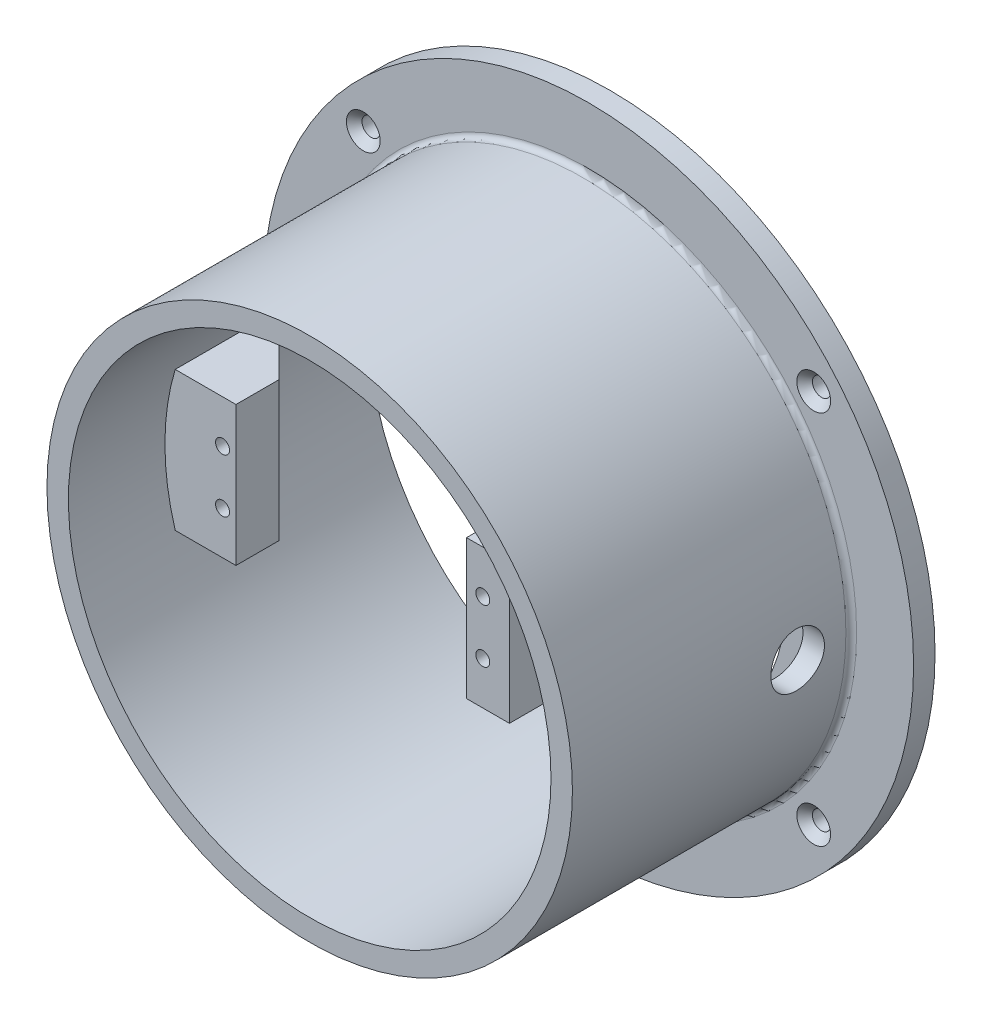
SolidWorks part; units mm, degrees
material "Acrylic (Medium-high impact)"
ref_plane "Front Plane" through (0, 0, 0) normal (0, 0, 1) x (1, 0, 0)
ref_plane "Top Plane" through (0, 0, 0) normal (0, 1, 0) x (1, 0, 0)
ref_plane "Right Plane" through (0, 0, 0) normal (1, 0, 0) x (0, 0, -1)
sketch "Sketch1" plane through (0, 0, 0) normal (0, 0, 1) x (1, 0, 0)
  circle A0 centre (0, 0) radius 60.625
  circle A1 centre (0, 0) radius 45
  dimension "D1" = 90
  dimension "D2" = 121.25
extrude "Boss-Extrude1" add sketch "Sketch1" along normal blind 4
sketch "Sketch2" plane through (0, 0, 4) normal (0, 0, 1) x (1, 0, 0)
  circle A0 centre (0, 0) radius 45 construction
  circle A1 centre (0, 0) radius 45
  circle A2 centre (0, 0) radius 49
  dimension "D1" = 4
extrude "Boss-Extrude2" add sketch "Sketch2" along normal blind 52
sketch "Sketch3" plane through (0, 0, 0) normal (0, 1, 0) x (1, 0, 0)
  line L0 (-45, -56) -> (45, -56) construction
  line L1 (-46.75, -30) -> (-31.75, -30)
  line L2 (-46.75, -30) -> (-46.75, -38)
  line L3 (-46.75, -38) -> (-31.75, -38)
  line L4 (-31.75, -30) -> (-31.75, -38)
  line L5 (11.25, 0) -> (19.25, 0)
  line L6 (11.25, 0) -> (11.25, -38)
  line L7 (11.25, -38) -> (19.25, -38)
  line L8 (19.25, 0) -> (19.25, -38)
  line L9 (45, 0) -> (-45, 0) construction
  line L10 (-31.75, -30) -> (-45, -16.75)
  line L11 (-45, -56) -> (-45, 0)
  dimension "D1" = 8
  dimension "D2" = 15
  dimension "D3" = 18
  dimension "D4" = 43
  dimension "D5" = 11.25
  dimension "D6" = 8
  dimension "D7" = 18
  dimension "D8" = 45
extrude "Boss-Extrude3" add sketch "Sketch3" along normal mid plane 26 contours L11 L3 L4 L1 | L11 L1 L10 | L8 L5 L6 L7
sketch "Sketch4" plane through (11.25, 0, 0) normal (-1, 0, 0) x (0, 0, 1)
  line L0 (38, -13) -> (38, 13) construction
  line L1 (5, 5) -> (29, 5)
  line L2 (5, 5) -> (5, -5)
  line L3 (5, -5) -> (29, -5)
  line L4 (29, 5) -> (29, -5)
  line L5 (0, 13) -> (0, -13) construction
  point P9 (5, 0)
  dimension "D1" = 9
  dimension "D2" = 10
  dimension "D3" = 5
extrude "Cut-Extrude1" cut sketch "Sketch4" against normal blind 26
sketch "Sketch5" plane through (11.25, 0, 0) normal (-1, 0, 0) x (0, 0, 1)
  circle A0 centre (14, 0) radius 5
  dimension "D1" = 10
  dimension "D2" = 14
extrude "Cut-Extrude2" cut sketch "Sketch5" against normal blind 74
sketch "Sketch6" plane through (0, 0, 38) normal (0, 0, 1) x (1, 0, 0)
  line L0 (-31.75, 13) -> (-31.75, -13) construction
  line L1 (-34.25, 5) -> (-34.25, -5) construction
  line L2 (14.2811, 5) -> (14.2811, -5) construction
  line L3 (-34.25, 5) -> (14.2811, 5) construction
  circle A0 centre (-34.25, 5) radius 1.3
  circle A1 centre (-34.25, -5) radius 1.3
  circle A2 centre (14.2811, 5) radius 1.3
  circle A3 centre (14.2811, -5) radius 1.3
  dimension "D1" = 2.6
  dimension "D2" = 2.5
  dimension "D3" = 48.5311
  dimension "D4" = 10
  dimension "D5" = 10
  dimension "D6" = 5
extrude "Cut-Extrude3" cut sketch "Sketch6" against normal blind 7.2
sketch "Sketch8" plane through (0, 0, 0) normal (0, 0, -1) x (-1, 0, 0)
  line L0 (-11.25, 13) -> (-11.25, -13) construction
  line L1 (-11.25, 13) -> (-11.25, -13)
  line L2 (-11.25, 13) -> (-25.2498, 37.2484)
  line L3 (-11.25, 0) -> (-45, 0) construction
  line L4 (-11.25, -13) -> (-25.2498, -37.2484)
  line L5 (-24.25, -19.5167) -> (-27.3618, -24.9065)
  line L7 (-24.25, 19.5167) -> (-27.3618, 24.9065)
  line L8 (-24.25, 19.5167) -> (-24.25, -19.5167)
  line L9 (-19.25, -10.8564) -> (-32.178, -33.2484) construction
  line L10 (-19.25, 10.8564) -> (-32.178, 33.2484) construction
  line L11 (-19.25, 10.8564) -> (-19.25, -10.8564) construction
  line L12 (-19.25, 13) -> (-19.25, -13) construction
  circle A0 centre (0, 0) radius 45 construction
  arc A1 (-25.2498, 37.2484) -> (-25.2498, -37.2484) centre (0, 0) ccw
  arc A2 (-27.3618, 24.9065) -> (-27.3618, -24.9065) centre (0, 0) ccw
  circle A3 centre (0, 0) radius 45 construction
  circle A4 centre (0, 0) radius 37 construction
  dimension "D1" = 60
  dimension "D3" = 5
  dimension "D2" = 8
extrude "Boss-Extrude4" add sketch "Sketch8" against normal blind 4
sketch "Sketch9" plane through (0, 0, 4) normal (0, 0, 1) x (1, 0, 0)
  line L1 (-42, 35) -> (42, 35) construction
  line L2 (-42, 35) -> (-42, -35) construction
  line L3 (-42, -35) -> (42, -35) construction
  line L4 (42, 35) -> (42, -35) construction
  line L5 (-42, 35) -> (42, -35) construction
  line L6 (-42, -35) -> (42, 35) construction
  point P0 (0, 0)
  dimension "D1" = 70
  dimension "D2" = 84
hole_wizard "CSK for M3 Countersunk Flat Head Screw1" positions "Sketch10" profile "Sketch11" countersink size "M3" standard "DIN"
sketch "Sketch10" plane through (0, 0, 4) normal (0, 0, 1) x (1, 0, 0)
  point P0 (-42, -35)
  point P3 (42, -35)
  point P6 (42, 35)
  point P9 (-42, 35)
sketch "Sketch11" plane through (-42, -35, 4) normal (1, 0, 0) x (0, -1, 0)
  line L0 (0, 0) -> (0, 5.0215)
  line L1 (0, 5.0215) -> (1.7, 4)
  line L2 (1.7, 4) -> (1.7, 1.45)
  line L3 (1.7, 1.45) -> (3.15, 0)
  line L5 (3.15, 0) -> (0, 0)
  line L6 (-1.7, 1.45) -> (-3.15, 0) construction
  line L10 (0, 5.0215) -> (-1.7, 4) construction
  line L11 (0, -6.35) -> (0, 107.95) construction
  dimension "Hole Dia." = 3.4
  dimension "Hole Depth" = 4
  dimension "Near C'Sink Dia." = 6.3
  dimension "Near C'Sink Angle" = 90
  dimension "Drill Angle" = 118
fillet "Fillet1" radius 1 1 edges at (49, 0, 4)
